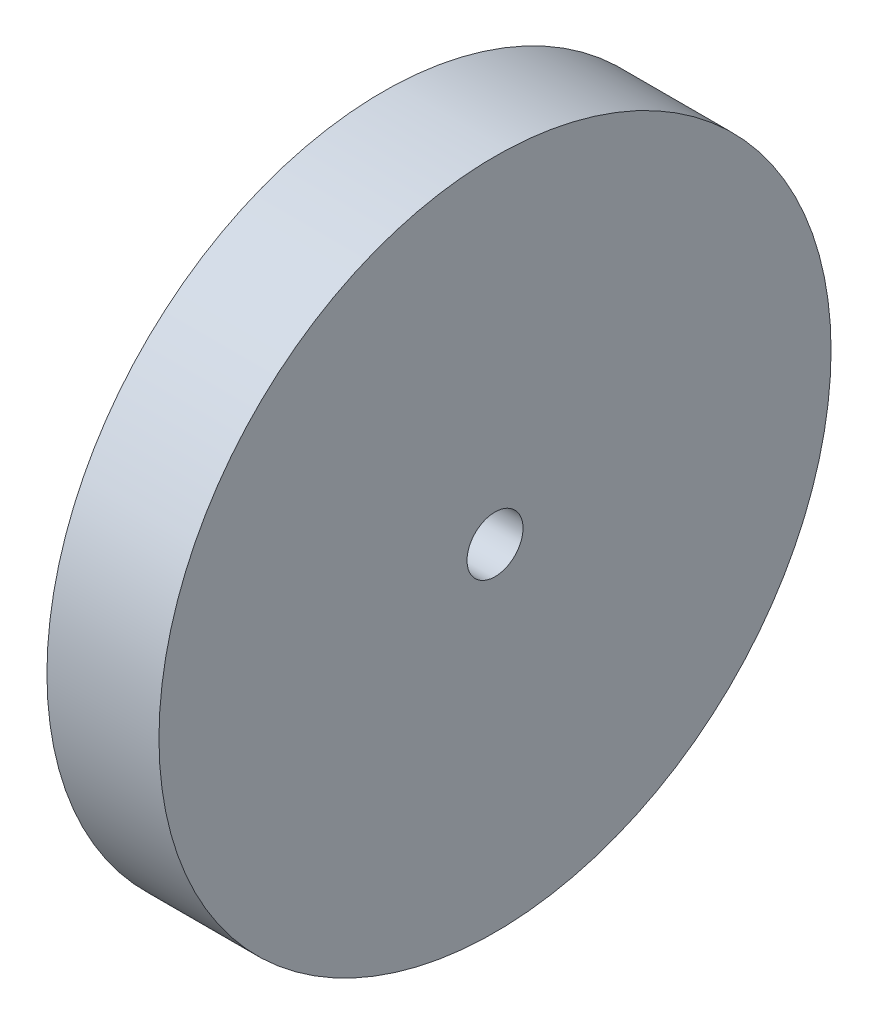
SolidWorks part; units mm, degrees
ref_plane "Front Plane" through (0, 0, 0) normal (0, 0, 1) x (1, 0, 0)
ref_plane "Top Plane" through (0, 0, 0) normal (0, 1, 0) x (1, 0, 0)
ref_plane "Right Plane" through (0, 0, 0) normal (1, 0, 0) x (0, 0, -1)
sketch "Sketch1" plane through (0, 0, 0) normal (1, 0, 0) x (0, 0, -1)
  circle A0 centre (0, 0) radius 38.1
  dimension "D1" = 76.2
extrude "Boss-Extrude1" add sketch "Sketch1" along normal blind 12.7
sketch "Sketch2" plane through (12.7, 0, 0) normal (1, 0, 0) x (0, 0, -1)
  circle A0 centre (0, 0) radius 3.175
extrude "Cut-Extrude1" cut sketch "Sketch2" against normal blind 12.7
